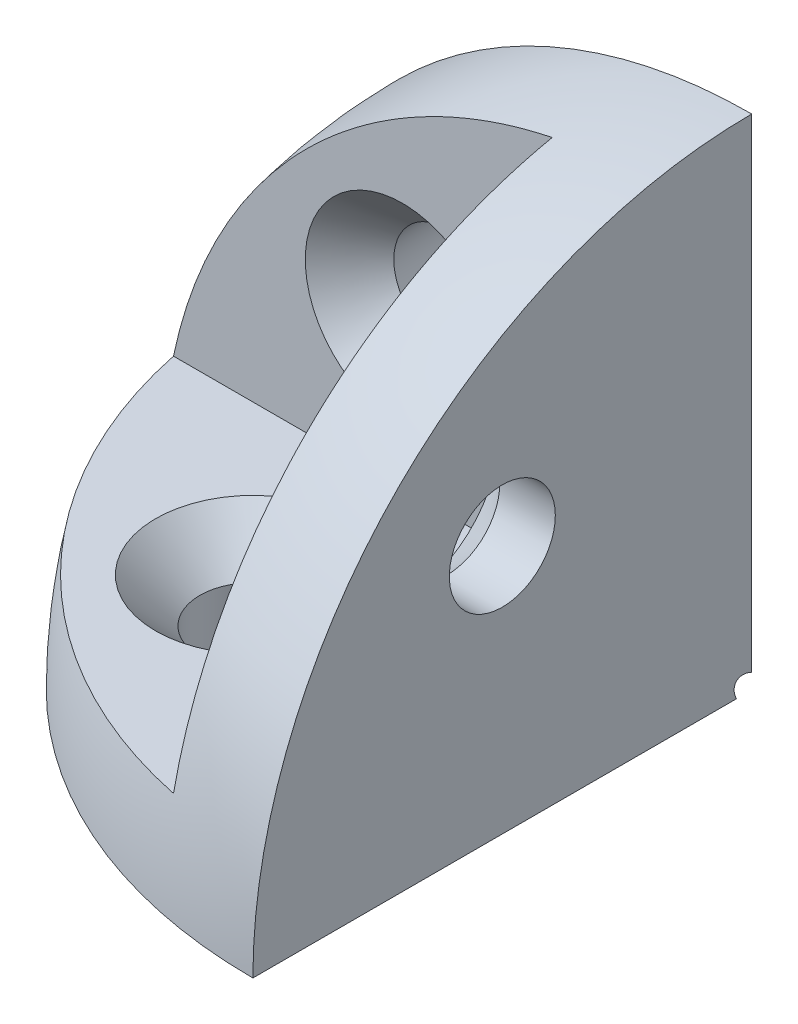
SolidWorks part; units mm, degrees
ref_plane "前视基准面" through (0, 0, 0) normal (0, 0, 1) x (1, 0, 0)
ref_plane "上视基准面" through (0, 0, 0) normal (0, 1, 0) x (1, 0, 0)
ref_plane "右视基准面" through (0, 0, 0) normal (1, 0, 0) x (0, 0, -1)
sketch "草图2" plane through (0, 0, 0) normal (0, 0, 1) x (1, 0, 0)
  line L0 (0, 0) -> (0, 40)
  line L1 (0, 0) -> (-40, 0)
  arc A0 (0, 40) -> (-40, 0) centre (0, 0) ccw
  dimension "D1" = 40
revolve "旋转2" add sketch "草图2" angle 90 about L0
shell "抽壳1" thickness 8
sketch "草图3" plane through (0, 0, 0) normal (1, 0, 0) x (0, 0, -1)
  line L0 (-40, 0) -> (0, 0) construction
  line L1 (0, 0) -> (0, 40) construction
  circle A0 centre (-20, 20) radius 4.25
  dimension "D3" = 8.5
  dimension "D1" = 20
  dimension "D2" = 20
extrude "切除-拉伸1" cut sketch "草图3" against normal through all
sketch "草图4" plane through (0, 0, 0) normal (0, 0, -1) x (-1, 0, 0)
  line L0 (0, 0) -> (0, 40) construction
  line L1 (40, 0) -> (0, 0) construction
  circle A0 centre (20, 20) radius 4.25
  dimension "D3" = 8.5
  dimension "D1" = 20
  dimension "D2" = 20
extrude "切除-拉伸2" cut sketch "草图4" against normal through all
sketch "草图5" plane through (0, 0, 0) normal (0, -1, 0) x (1, 0, 0)
  line L0 (0, 40) -> (0, 0) construction
  line L1 (-40, 0) -> (0, 0) construction
  circle A0 centre (-20, 20) radius 4.25
  dimension "D3" = 8.5
  dimension "D1" = 20
  dimension "D2" = 20
extrude "切除-拉伸3" cut sketch "草图5" against normal through all
chamfer "倒角1" distance 3.55 angle 45 1 edges at (-8, 20, 15.75)
chamfer "倒角2" distance 3.55 angle 45 1 edges at (-15.75, 20, 8)
chamfer "倒角3" distance 3.55 angle 45 1 edges at (-20, 8, 24.25)
ref_plane "基准面2" through (0, 0, 0) normal (-0.7071, 0, -0.7071) x (-0.7071, 0, 0.7071)
sketch "草图9" plane through (0, 0, 0) normal (-0.7071, 0, -0.7071) x (-0.7071, 0, 0.7071)
  line L0 (-5.259, -3.7187) -> (16.6252, 11.7558)
  line L2 (-4.5923, -4.472) -> (17.2025, 10.9393)
  line L3 (-4.5923, -4.472) -> (-5.259, -3.7187)
  line L4 (0, 0) -> (16.6252, 11.7558) construction
  line L5 (0.5774, -0.8165) -> (17.2025, 10.9393) construction
  line L6 (16.6252, 11.7558) -> (17.2025, 10.9393)
  dimension "D1" = 1
revolve "切除-旋转2" cut sketch "草图9" angle 360 about L0
